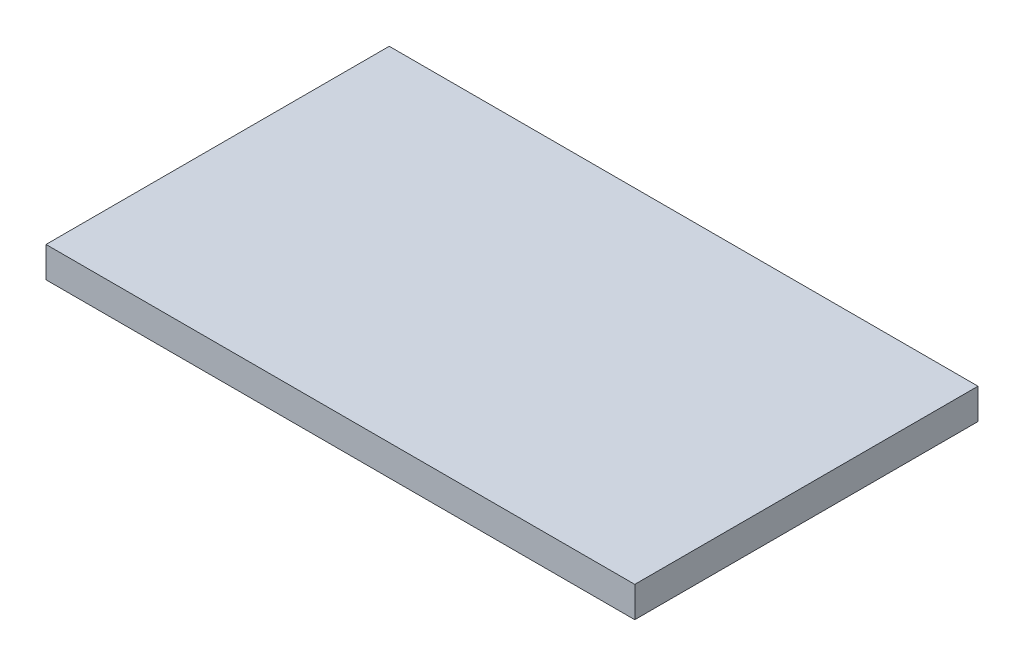
SolidWorks part; units mm, degrees
ref_plane "Front Plane" through (0, 0, 0) normal (0, 0, 1) x (1, 0, 0)
ref_plane "Top Plane" through (0, 0, 0) normal (0, 1, 0) x (1, 0, 0)
ref_plane "Right Plane" through (0, 0, 0) normal (1, 0, 0) x (0, 0, -1)
sketch "Sketch1" plane through (0, 0, 0) normal (0, 1, 0) x (1, 0, 0)
  line L1 (0, 0) -> (38.44, 0)
  line L2 (0, 0) -> (0, -22.41)
  line L3 (0, -22.41) -> (38.44, -22.41)
  line L4 (38.44, 0) -> (38.44, -22.41)
  dimension "D1" = 38.44
  dimension "D2" = 22.41
extrude "Boss-Extrude1" add sketch "Sketch1" along normal blind 2
